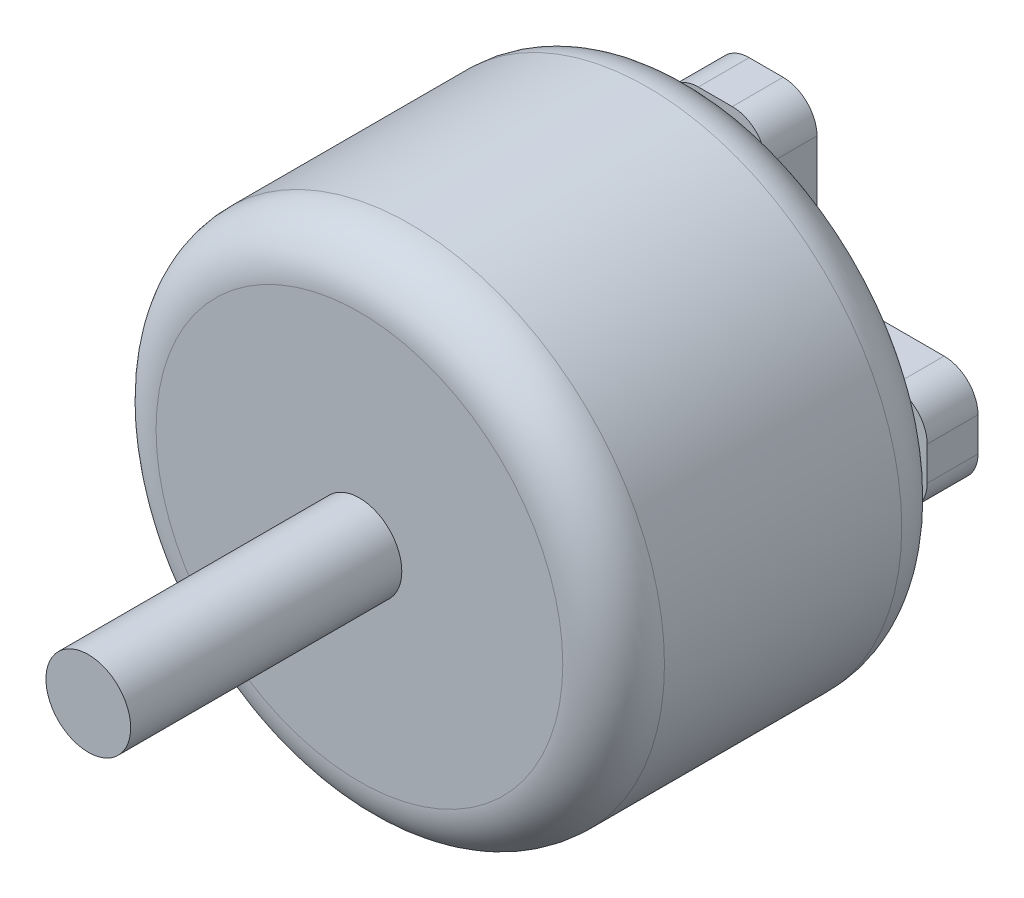
SolidWorks part; units mm, degrees
ref_plane "Front Plane" through (0, 0, 0) normal (0, 0, 1) x (1, 0, 0)
ref_plane "Top Plane" through (0, 0, 0) normal (0, 1, 0) x (1, 0, 0)
ref_plane "Right Plane" through (0, 0, 0) normal (1, 0, 0) x (0, 0, -1)
sketch "Sketch1" plane through (0, 0, 0) normal (0, 0, 1) x (1, 0, 0)
  line L0 (-71.7817, -74.7817) -> (-67.2817, -74.7817)
  line L1 (-78.7817, -65.2817) -> (-76.7817, -65.2817)
  line L2 (-80.7817, -67.2817) -> (-80.7817, -71.7817)
  line L3 (-78.7817, -90.2817) -> (-76.7817, -90.2817)
  line L4 (-74.7817, -67.2817) -> (-74.7817, -71.7817)
  line L5 (-88.2817, -74.7817) -> (-83.7817, -74.7817)
  line L6 (-90.2817, -76.7817) -> (-90.2817, -78.7817)
  line L7 (-88.2817, -80.7817) -> (-83.7817, -80.7817)
  line L8 (-65.2817, -76.7817) -> (-65.2817, -78.7817)
  line L9 (-80.7817, -83.7817) -> (-80.7817, -88.2817)
  line L10 (-74.7817, -83.7817) -> (-74.7817, -88.2817)
  line L11 (-71.7817, -80.7817) -> (-67.2817, -80.7817)
  arc A4 (-80.7817, -83.7817) -> (-83.7817, -80.7817) centre (-83.7817, -83.7817) ccw
  arc A5 (-74.7817, -83.7817) -> (-71.7817, -80.7817) centre (-71.7817, -83.7817) cw
  arc A6 (-71.7817, -74.7817) -> (-74.7817, -71.7817) centre (-71.7817, -71.7817) cw
  arc A7 (-83.7817, -74.7817) -> (-80.7817, -71.7817) centre (-83.7817, -71.7817) ccw
  arc A8 (-78.7817, -65.2817) -> (-80.7817, -67.2817) centre (-78.7817, -67.2817) ccw
  arc A9 (-76.7817, -65.2817) -> (-74.7817, -67.2817) centre (-76.7817, -67.2817) cw
  arc A10 (-67.2817, -74.7817) -> (-65.2817, -76.7817) centre (-67.2817, -76.7817) cw
  arc A11 (-67.2817, -80.7817) -> (-65.2817, -78.7817) centre (-67.2817, -78.7817) ccw
  arc A12 (-76.7817, -90.2817) -> (-74.7817, -88.2817) centre (-76.7817, -88.2817) ccw
  arc A13 (-80.7817, -88.2817) -> (-78.7817, -90.2817) centre (-78.7817, -88.2817) ccw
  arc A14 (-90.2817, -78.7817) -> (-88.2817, -80.7817) centre (-88.2817, -78.7817) ccw
  arc A15 (-88.2817, -74.7817) -> (-90.2817, -76.7817) centre (-88.2817, -76.7817) ccw
  circle A16 centre (-77.7817, -68.2817) radius 1.6
  circle A17 centre (-68.2817, -77.7817) radius 1.6
  circle A18 centre (-77.7817, -87.2817) radius 1.6
  circle A19 centre (-87.2817, -77.7817) radius 1.6
  point P24 (-74.7817, -80.7817)
  point P39 (-74.7817, -90.2817)
  point P42 (-80.7817, -90.2817)
  point P45 (-90.2817, -80.7817)
  point P48 (-90.2817, -74.7817)
  dimension "D9" = 3
  dimension "D10" = 2
  dimension "D2" = 6
  dimension "D3" = 6
extrude "Boss-Extrude1" add sketch "Sketch1" along normal blind 3
sketch "Sketch2" plane through (0, 0, 3) normal (0, 0, 1) x (1, 0, 0)
  line L0 (-77.7817, -68.2817) -> (-77.7817, -77.7817) construction
  line L1 (-68.2817, -77.7817) -> (-77.7817, -77.7817) construction
  circle A0 centre (-77.7817, -77.7817) radius 2.852
extrude "Boss-Extrude2" add sketch "Sketch2" along normal blind 1
sketch "Sketch3" plane through (0, 0, 4) normal (0, 0, 1) x (1, 0, 0)
  circle A0 centre (-77.7817, -77.7817) radius 15
extrude "Boss-Extrude3" add sketch "Sketch3" along normal blind 20
sketch "Sketch4" plane through (0, 0, 24) normal (0, 0, 1) x (1, 0, 0)
  circle A0 centre (-77.7817, -77.7817) radius 2.5
extrude "Boss-Extrude4" add sketch "Sketch4" along normal blind 16
fillet "Fillet1" radius 3 2 edges at (-62.7817, -77.7817, 24) (-62.7817, -77.7817, 4)
